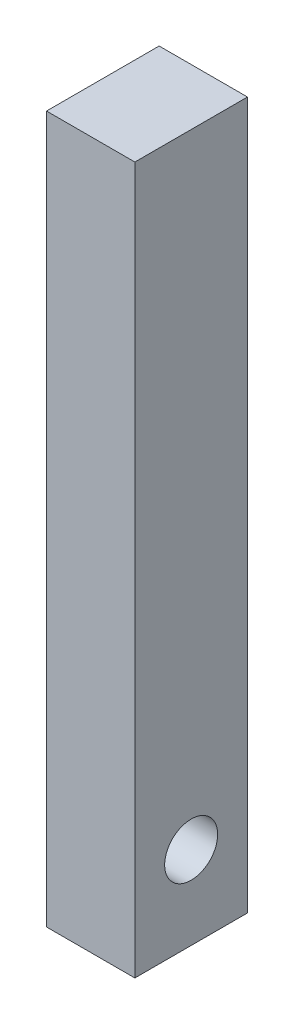
SolidWorks part; units mm, degrees
ref_plane "Ebene vorne" through (0, 0, 0) normal (0, 0, 1) x (1, 0, 0)
ref_plane "Ebene oben" through (0, 0, 0) normal (0, 1, 0) x (1, 0, 0)
ref_plane "Ebene rechts" through (0, 0, 0) normal (1, 0, 0) x (0, 0, -1)
sketch "Skizze1" plane through (0, 0, 0) normal (0, 0, 1) x (1, 0, 0)
  line L1 (-5.9493, 14.0025) -> (-15.9493, 14.0025)
  line L2 (-5.9493, 14.0025) -> (-5.9493, -65.9975)
  line L3 (-5.9493, -65.9975) -> (-15.9493, -65.9975)
  line L4 (-15.9493, 14.0025) -> (-15.9493, -65.9975)
  dimension "D1" = 80
  dimension "D2" = 10
extrude "Aufsatz-Linear austragen1" add sketch "Skizze1" along normal blind 12.75
hole_wizard "Ø6.0 (6) Durchmesser Bohrung1" positions "Skizze4" profile "Skizze5" hole size "Ø6.0" standard "DIN" end condition up to next
sketch "Skizze4" plane through (-5.9493, 0, 0) normal (1, 0, 0) x (0, 0, -1)
  line L0 (0, -65.9975) -> (0, 14.0025) construction
  line L2 (-12.75, -65.9975) -> (0, -65.9975) construction
  point P0 (-6.375, -56.5975)
  dimension "D1" = 6.375
  dimension "D2" = 9.4
sketch "Skizze5" plane through (-5.9493, -56.5975, 6.375) normal (0, 1, 0) x (0, 0, -1)
  line L0 (0, 0) -> (0, 10)
  line L1 (0, 10) -> (3, 10)
  line L2 (3, 10) -> (3, 0)
  line L5 (3, 0) -> (0, 0)
  line L11 (0, -6.35) -> (0, 107.95) construction
  dimension "Bohrerdurchmesser" = 6
  dimension "Bohrungstiefe" = 10
